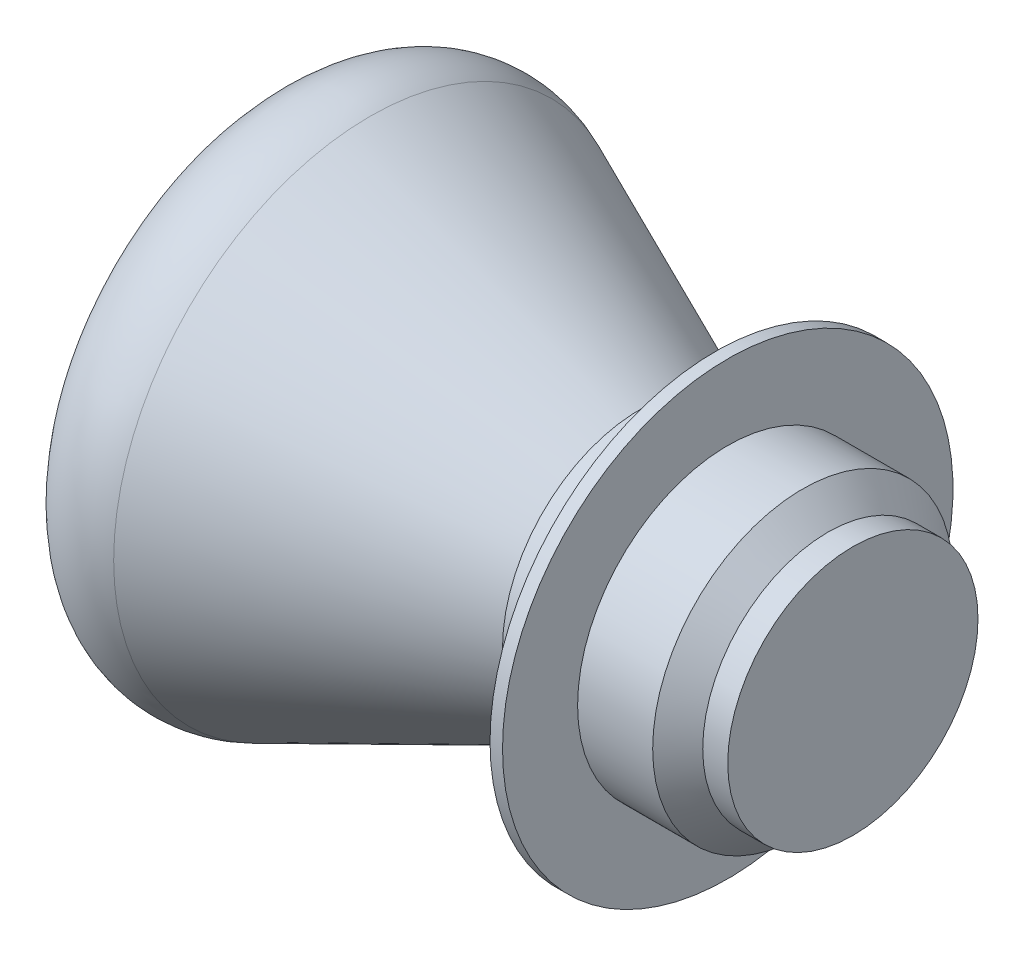
SolidWorks part; units mm, degrees
ref_plane "Front Plane" through (0, 0, 0) normal (0, 0, 1) x (1, 0, 0)
ref_plane "Top Plane" through (0, 0, 0) normal (0, 1, 0) x (1, 0, 0)
ref_plane "Right Plane" through (0, 0, 0) normal (1, 0, 0) x (0, 0, -1)
sketch "Sketch2" plane through (0, 0, 0) normal (0, 0, 1) x (1, 0, 0)
  line L0 (0, 0) -> (5.5, 0)
  line L1 (5.5, 0) -> (5.5, 5)
  line L2 (5.5, 5) -> (4.5, 5)
  line L3 (4.5, 5) -> (3.5, 6)
  line L4 (3.5, 6) -> (0.5, 6)
  line L5 (0.5, 6) -> (0.5, 9)
  line L6 (0.5, 9) -> (0, 9)
  line L7 (0, 9) -> (0, 6)
  line L8 (0, 6) -> (-2, 6)
  line L9 (-2, 6) -> (-2, 5.5)
  line L10 (-2, 5.5) -> (0, 5.5)
  line L11 (0, 5.5) -> (0, 0)
  dimension "D1" = 1
  dimension "D2" = 1
  dimension "D3" = 1
  dimension "D4" = 3
  dimension "D5" = 5
  dimension "D6" = 5.5
  dimension "D7" = 2
  dimension "D8" = 0.5
  dimension "D9" = 3
revolve "Revolve1" add sketch "Sketch2" angle 360 about L0
sketch "Sketch3" plane through (0, 0, 0) normal (0, 0, 1) x (1, 0, 0)
  line L0 (0, 0) -> (-16.0552, 0) construction
  line L1 (0, 5.5) -> (-3, 5.5)
  line L2 (-3, 5.5) -> (-13.7923, 10.2462)
  line L3 (-19.122, 0) -> (0, 0)
  line L4 (0, 0) -> (0, 5.5)
  arc A0 (-17.8687, 8.3779) -> (-19.122, 0) centre (9.5064, 0) ccw
  arc A1 (-13.7923, 10.2462) -> (-17.8687, 8.3779) centre (-15, 7.5) ccw
  dimension "D1" = 3
  dimension "D2" = 15
  dimension "D3" = 2
  dimension "D5" = 3
revolve "Revolve2" add sketch "Sketch3" angle 360 about L3
